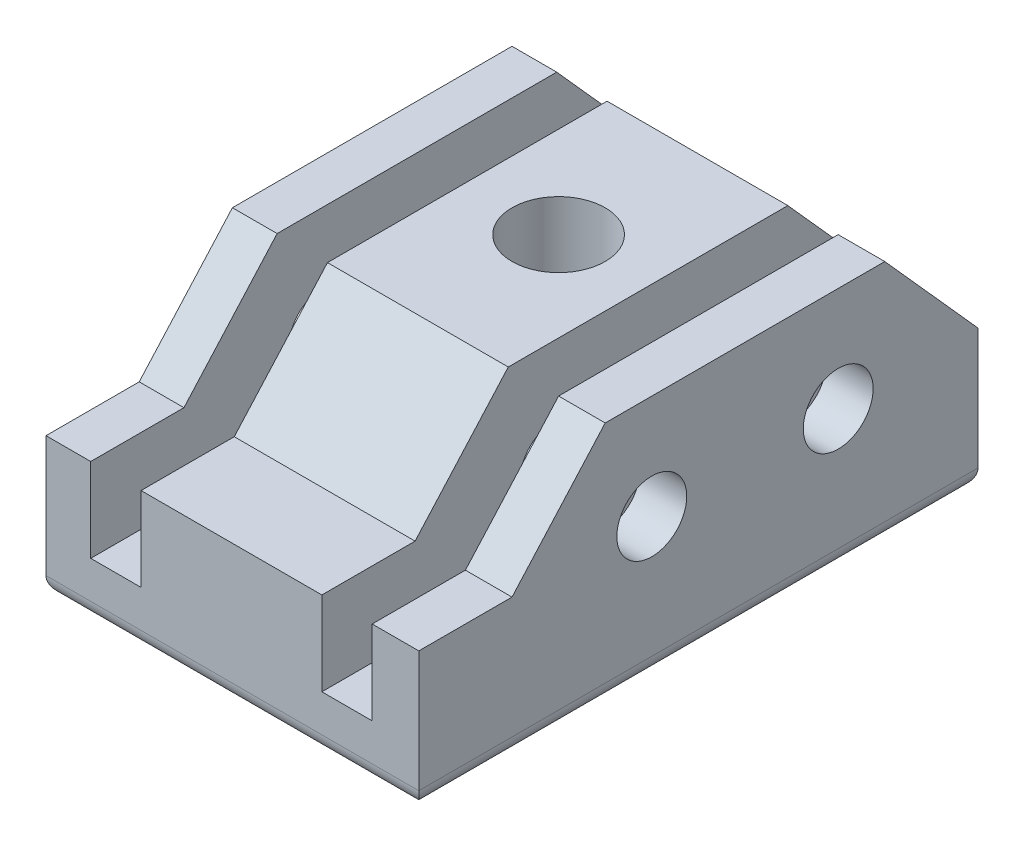
SolidWorks part; units mm, degrees
ref_plane "Front Plane" through (0, 0, 0) normal (0, 0, 1) x (1, 0, 0)
ref_plane "Top Plane" through (0, 0, 0) normal (0, 1, 0) x (1, 0, 0)
ref_plane "Right Plane" through (0, 0, 0) normal (1, 0, 0) x (0, 0, -1)
sketch "Sketch1" plane through (0, 0, 0) normal (1, 0, 0) x (0, 0, -1)
  line L1 (0, 0) -> (63.5, 0)
  line L2 (0, 0) -> (0, 6.35)
  line L3 (0, 6.35) -> (63.5, 6.35)
  line L4 (63.5, 0) -> (63.5, 6.35)
  dimension "D1" = 6.35
  dimension "D2" = 63.5
extrude "Boss-Extrude1" add sketch "Sketch1" against normal blind 50.8
sketch "Sketch2" plane through (0, 0, 0) normal (1, 0, 0) x (0, 0, -1)
  line L0 (0, 6.35) -> (0, 19.05)
  line L1 (0, 19.05) -> (12.7, 33.249)
  line L2 (12.7, 33.249) -> (50.8, 33.249)
  line L3 (50.8, 33.249) -> (63.5, 19.05)
  line L4 (63.5, 19.05) -> (63.5, 6.35)
  line L5 (63.5, 6.35) -> (0, 6.35)
  point P7 (31.75, 33.249)
  point P10 (31.75, 6.35)
  dimension "D1" = 38.1
  dimension "D2" = 12.7
  dimension "D3" = 12.7
  dimension "D4" = 19.05
  dimension "D5" = 19.05
extrude "Boss-Extrude2" add sketch "Sketch2" against normal blind 50.8
sketch "Sketch10" plane through (0, 0, -63.5) normal (0, 0, -1) x (-1, 0, 0)
  line L1 (50.8, 33.249) -> (0, 33.249) construction
  line L3 (6.35, 7.62) -> (6.35, 33.249)
  line L4 (6.35, 33.249) -> (13.208, 33.249)
  line L5 (13.208, 7.62) -> (13.208, 33.249)
  line L6 (6.35, 7.62) -> (13.208, 7.62)
  line L8 (50.8, 0) -> (0, 0) construction
  point P11 (13.208, 7.62)
  dimension "D1" = 7.62
  dimension "D2" = 6.858
  dimension "D3" = 6.35
extrude "Cut-Extrude1" cut sketch "Sketch10" against normal through all
pattern_linear "LPattern3" count 2 spacing 31.496 along (-1, 0, 0) of "Cut-Extrude1"
sketch "Sketch11" plane through (0, 0, 0) normal (1, 0, 0) x (0, 0, -1)
  circle A0 centre (19.05, 19.05) radius 4.7625
  circle A1 centre (19.05, 19.05) radius 7.9375 construction
  circle A2 centre (44.45, 19.05) radius 4.7625
  circle A3 centre (44.45, 19.05) radius 7.9375 construction
  dimension "D1" = 9.525
  dimension "D3" = 15.875
  dimension "D4" = 9.525
  dimension "D6" = 15.875
  dimension "D2" = 6.35
  dimension "D5" = 6.35
extrude "Cut-Extrude2" cut sketch "Sketch11" against normal through all
sketch "Sketch14" plane through (0, 33.249, 0) normal (0, 1, 0) x (1, 0, 0)
  line L3 (-37.846, 12.7) -> (-37.846, 50.8) construction
  point P0 (-25.4, 31.75)
  point P4 (-37.846, 31.75)
  dimension "D1" = 12.446
sketch "Sketch17" plane through (0, 40.0201, -44.7438) normal (0, 0.6667, -0.7454) x (-1, 0, 0)
  line L0 (13.208, -28.1343) -> (13.208, -9.0843) construction
  line L1 (37.846, -9.0843) -> (13.208, -9.0843) construction
  point P0 (25.527, -18.6093)
  point P4 (13.208, -18.6093)
  point P7 (25.527, -9.0843)
sketch "Sketch18" plane through (0, 8.4667, 9.466) normal (0, 0.6667, 0.7454) x (1, 0, 0)
  line L0 (-13.208, 33.249) -> (-13.208, 14.199) construction
  line L1 (-37.846, 33.249) -> (-13.208, 33.249) construction
  point P0 (-25.527, 23.724)
  point P1 (-25.527, 23.724)
  point P4 (-13.208, 23.724)
  point P7 (-25.527, 33.249)
ref_plane "Plane2" through (0, 33.02, 0) normal (0, -1, 0) x (-1, 0, 0)
fillet "Fillet1" [suppressed] radius 2.54
sketch "Sketch22" plane through (0, 0, 0) normal (0, 0, 1) x (1, 0, 0)
  line L0 (-50.8, 19.05) -> (-50.8, 0) construction
  line L1 (0, 0) -> (-50.8, 0)
  line L2 (0, 0) -> (0, 7.62)
  line L3 (-6.35, 7.62) -> (-13.208, 7.62)
  line L4 (-50.8, 0) -> (-50.8, 7.62)
  line L5 (-37.846, 7.62) -> (-37.846, 19.05)
  line L6 (-37.846, 19.05) -> (-13.208, 19.05)
  line L7 (-13.208, 19.05) -> (-13.208, 7.62)
  line L8 (-37.846, 7.62) -> (-44.704, 7.62)
  line L9 (-50.8, 7.62) -> (-50.8, 19.05)
  line L10 (-50.8, 19.05) -> (-44.704, 19.05)
  line L11 (-44.704, 19.05) -> (-44.704, 7.62)
  line L12 (-6.35, 7.62) -> (-6.35, 19.05)
  line L13 (-6.35, 19.05) -> (0, 19.05)
  line L14 (0, 19.05) -> (0, 7.62)
extrude "Boss-Extrude3" add sketch "Sketch22" along normal blind 12.7
sketch "Sketch23" plane through (0, 33.249, 0) normal (0, 1, 0) x (1, 0, 0)
  line L0 (-25.4, 63.5) -> (-25.4, -12.7) construction
  line L1 (-50.8, 63.5) -> (0, 63.5) construction
  line L2 (-50.8, -12.7) -> (0, -12.7) construction
  circle A0 centre (-25.4, 31.75) radius 6.35
  point P15 (-34.579, 50.8)
  dimension "D1" = 12.7
extrude "Cut-Extrude6" cut sketch "Sketch23" against normal through all
fillet "Fillet2" radius 2.54 4 edges at (-25.4, 0, -63.5) (0, 0, -25.4) (-50.8, 0, -25.4) (-25.4, 0, 12.7)
sketch "Sketch24" plane through (0, 0, 0) normal (0, -1, 0) x (1, 0, 0)
  line L0 (-20.4, -46.15) -> (-30.4, -46.15) construction
  line L1 (-25.4, -60.96) -> (-25.4, 10.16) construction
  line L2 (-48.26, -60.96) -> (-2.54, -60.96) construction
  line L3 (-2.54, 10.16) -> (-48.26, 10.16) construction
  line L4 (-20.4, 3.35) -> (-30.4, 3.35) construction
  circle A1 centre (-30.4, -46.15) radius 3.05
  circle A2 centre (-20.4, -46.15) radius 3.05
  circle A3 centre (-20.4, 3.35) radius 3.05
  circle A4 centre (-30.4, 3.35) radius 3.05
  circle A5 centre (-25.4, -31.75) radius 6.35 construction
  point P3 (-25.4, -46.15)
  point P12 (-25.4, 3.35)
  dimension "D2" = 6.1
  dimension "D1" = 10
  dimension "D3" = 49.5
  dimension "D4" = 14.4
extrude "Cut-Extrude7" cut sketch "Sketch24" against normal blind 10
